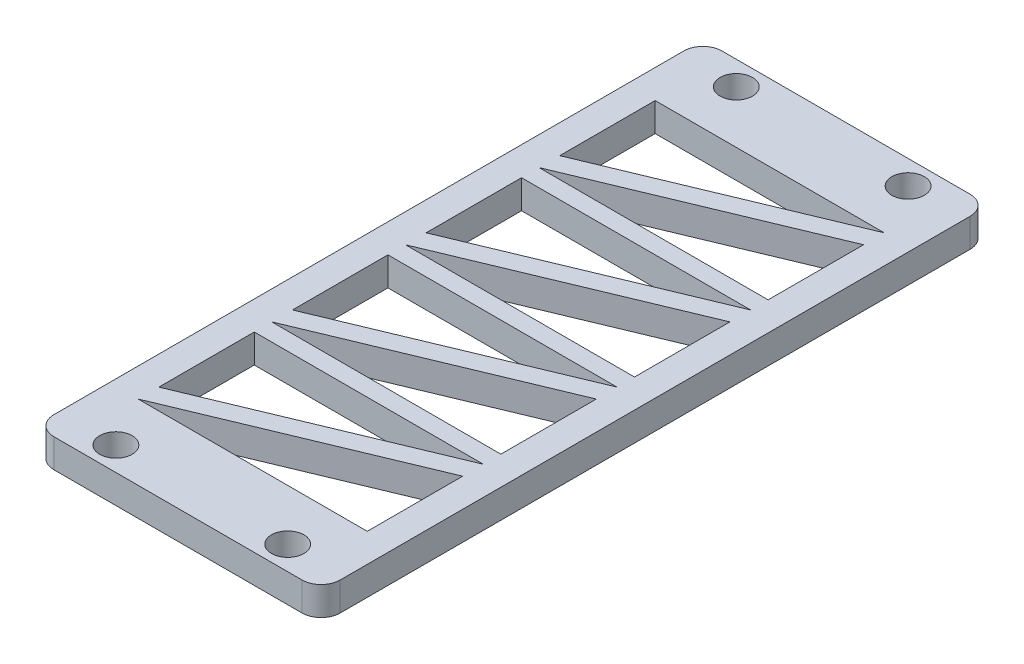
SolidWorks part; units mm, degrees
ref_plane "Front Plane" through (0, 0, 0) normal (0, 0, 1) x (1, 0, 0)
ref_plane "Top Plane" through (0, 0, 0) normal (0, 1, 0) x (1, 0, 0)
ref_plane "Right Plane" through (0, 0, 0) normal (1, 0, 0) x (0, 0, -1)
sketch "Sketch1" plane through (0, 0, 0) normal (0, 1, 0) x (1, 0, 0)
  line L0 (-29.9635, 0) -> (27.5506, 0) construction
  line L1 (0, 23.9774) -> (0, -20.7387) construction
  line L2 (-15, 35) -> (0, 35)
  line L3 (0, 35) -> (15, 35)
  line L4 (15, 35) -> (15, 0)
  line L5 (15, 0) -> (15, -35)
  line L6 (15, -35) -> (0, -35)
  line L7 (0, -35) -> (-15, -35)
  line L8 (-15, -35) -> (-15, 0)
  line L9 (-15, 0) -> (-15, 35)
  dimension "D1" = 15
  dimension "D2" = 35
extrude "Boss-Extrude1" add sketch "Sketch1" along normal blind 3
sketch "Sketch2" plane through (0, 3, 0) normal (0, 1, 0) x (1, 0, 0)
  line L0 (-15, 0) -> (15, 0) construction
  line L1 (-15, 35) -> (-15, -35) construction
  line L2 (15, -35) -> (15, 35) construction
  line L3 (15, 35) -> (-15, 35) construction
  line L4 (0, 35) -> (0, -35) construction
  line L5 (-15, -35) -> (15, -35) construction
  circle A0 centre (-9, 32.5) radius 1.7
  circle A1 centre (9, 32.5) radius 1.7
  circle A2 centre (9, -32.5) radius 1.7
  circle A3 centre (-9, -32.5) radius 1.7
  point P20 (0, 0)
  dimension "D1" = 2.5
  dimension "D2" = 18
extrude "Cut-Extrude1" cut sketch "Sketch2" against normal through all and the other way through all
sketch "Sketch3" plane through (0, 3, 0) normal (0, 1, 0) x (1, 0, 0)
  line L0 (0, 35) -> (0, -35) construction
  line L1 (15, 35) -> (-15, 35) construction
  line L2 (-15, -35) -> (15, -35) construction
  line L3 (-12, 27) -> (0, 27)
  line L4 (0, 27) -> (12, 27)
  line L5 (12, 27) -> (-12, 17)
  line L6 (-12, 17) -> (-12, 27)
  line L13 (-12, 14.8333) -> (12, 24.8333)
  line L15 (12, 14.8333) -> (12, 24.8333)
  line L16 (-12, 14.8333) -> (12, 14.8333)
  line L17 (-12, 13) -> (0, 13)
  line L18 (0, 13) -> (12, 13)
  line L19 (12, 13) -> (-12, 3)
  line L20 (-12, 3) -> (-12, 13)
  line L21 (-12, 0.8333) -> (12, 10.8333)
  line L22 (12, 0.8333) -> (12, 10.8333)
  line L23 (-12, 0.8333) -> (12, 0.8333)
  line L24 (0, 21) -> (0, -49) construction
  line L25 (-12, -1) -> (0, -1)
  line L26 (0, -1) -> (12, -1)
  line L27 (12, -1) -> (-12, -11)
  line L28 (-12, -11) -> (-12, -1)
  line L29 (-12, -13.1667) -> (12, -3.1667)
  line L30 (12, -13.1667) -> (12, -3.1667)
  line L31 (-12, -13.1667) -> (12, -13.1667)
  line L32 (0, 7) -> (0, -63) construction
  line L33 (-12, -15) -> (0, -15)
  line L34 (0, -15) -> (12, -15)
  line L35 (12, -15) -> (-12, -25)
  line L36 (-12, -25) -> (-12, -15)
  line L37 (-12, -27.1667) -> (12, -17.1667)
  line L38 (12, -27.1667) -> (12, -17.1667)
  line L39 (-12, -27.1667) -> (12, -27.1667)
  line L40 (0, -7) -> (0, -77) construction
  dimension "D1" = 10
  dimension "D2" = 8
  dimension "D3" = 2
  dimension "D4" = 12
  dimension "D5" = 4
extrude "Cut-Extrude2" cut sketch "Sketch3" against normal through all and the other way through all
fillet "Fillet1" radius 2 4 edges at (-15, 1.5, -35) (15, 1.5, -35) (15, 1.5, 35) (-15, 1.5, 35)
